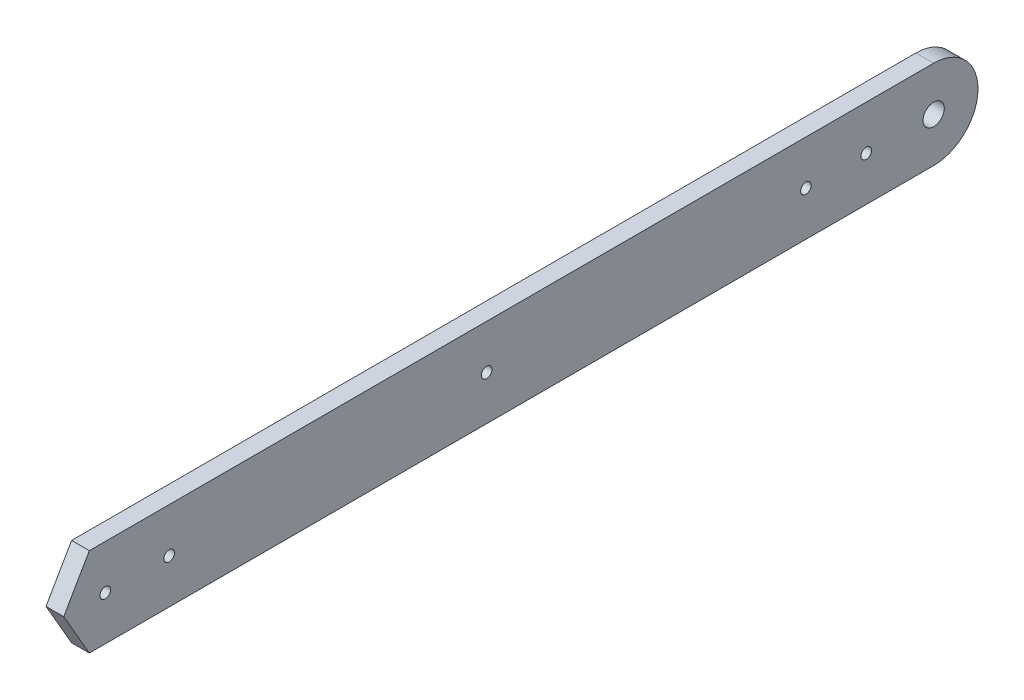
SolidWorks part; units mm, degrees
ref_plane "Front Plane" through (0, 0, 0) normal (0, 0, 1) x (1, 0, 0)
ref_plane "Top Plane" through (0, 0, 0) normal (0, 1, 0) x (1, 0, 0)
ref_plane "Right Plane" through (0, 0, 0) normal (1, 0, 0) x (0, 0, -1)
sketch "Sketch1" plane through (0, 0, 0) normal (0, 0, 1) x (1, 0, 0)
  line L1 (-2.5, -12.5) -> (2.5, -12.5)
  line L2 (-2.5, -12.5) -> (-2.5, 12.5)
  line L3 (-2.5, 12.5) -> (2.5, 12.5)
  line L4 (2.5, -12.5) -> (2.5, 12.5)
  line L5 (-2.5, -12.5) -> (2.5, 12.5) construction
  line L6 (-2.5, 12.5) -> (2.5, -12.5) construction
  point P0 (0, 0)
  dimension "D2" = 5
  dimension "D3" = 25
extrude "Boss-Extrude1" add sketch "Sketch1" along normal blind 258.5
sketch "Sketch2" plane through (2.5, 0, 0) normal (1, 0, 0) x (0, 0, -1)
  line L0 (-258.5, 0) -> (0, 0) construction
  line L1 (-258.5, -12.5) -> (-258.5, 12.5) construction
  line L2 (0, -12.5) -> (0, 12.5) construction
  line L3 (-12.5, 12.5) -> (5.5, 12.5)
  line L4 (5.5, 12.5) -> (5.5, -12.5)
  line L5 (5.5, -12.5) -> (-12.5, -12.5)
  line L9 (-257.7169, 0) -> (-250.5, 12.5)
  line L10 (-258.5, 12.5) -> (0, 12.5) construction
  line L11 (-250.5, 12.5) -> (-258.5, 12.5)
  line L12 (-258.5, 12.5) -> (-258.5, -12.5)
  line L13 (-258.5, -12.5) -> (-250.5, -12.5)
  line L14 (-258.5, -12.5) -> (0, -12.5) construction
  line L15 (-250.5, -12.5) -> (-257.7169, 0)
  circle A0 centre (-12.5, 0) radius 3
  circle A1 centre (-246, 0) radius 1.5
  circle A2 centre (-228, 0) radius 1.5
  arc A3 (-12.5, -12.5) -> (-12.5, 12.5) centre (-12.5, 0) ccw
  circle A5 centre (-48.5, 0) radius 1.5
  circle A6 centre (-31.5, 0) radius 1.5
  circle A7 centre (-138.5, 0) radius 1.5
  dimension "D1" = 6
  dimension "D2" = 12.5
  dimension "D4" = 3
  dimension "D5" = 18
  dimension "D7" = 120
  dimension "D8" = 19
  dimension "D9" = 17
  dimension "D11" = 90
  dimension "D3" = 12.5
  dimension "D6" = 18
  dimension "D10" = 4.5
extrude "Cut-Extrude1" cut sketch "Sketch2" against normal through all
